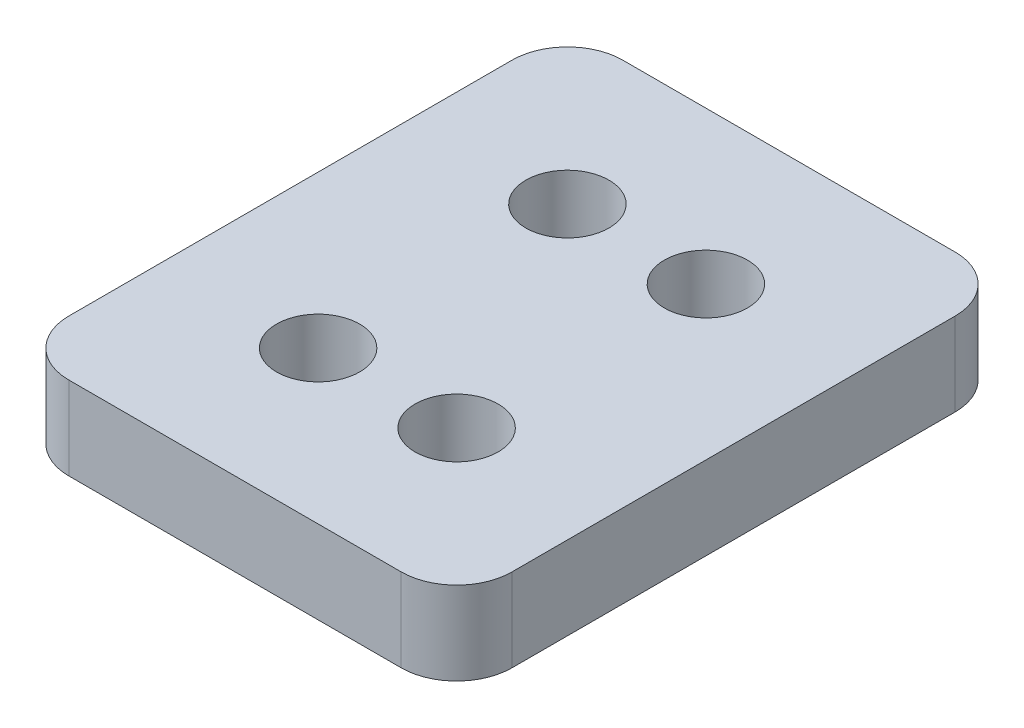
SolidWorks part; units mm, degrees
ref_plane "Plano frontal" through (0, 0, 0) normal (0, 0, 1) x (1, 0, 0)
ref_plane "Plano superior" through (0, 0, 0) normal (0, 1, 0) x (1, 0, 0)
ref_plane "Plano direito" through (0, 0, 0) normal (1, 0, 0) x (0, 0, -1)
sketch "Sketch1" plane through (0, 0, 0) normal (0, 1, 0) x (1, 0, 0)
  line L1 (-8, -10) -> (8, -10)
  line L2 (-8, -10) -> (-8, 10)
  line L3 (-8, 10) -> (8, 10)
  line L4 (8, -10) -> (8, 10)
  line L5 (-8, -10) -> (8, 10) construction
  line L6 (-8, 10) -> (8, -10) construction
  point P0 (0, 0)
  dimension "D1" = 16
  dimension "D2" = 20
extrude "Boss-Extrude1" add sketch "Sketch1" along normal mid plane 3
sketch "Sketch2" plane through (0, 1.5, 0) normal (0, 1, 0) x (1, 0, 0)
  circle A0 centre (2.5, -4.5) radius 1.5
  circle A1 centre (-2.5, -4.5) radius 1.5
  circle A2 centre (2.5, 4.5) radius 1.5
  circle A3 centre (-2.5, 4.5) radius 1.5
  dimension "D1" = 3
  dimension "D2" = 3
  dimension "D3" = 3
  dimension "D4" = 3
  dimension "D5" = 4.5
  dimension "D6" = 4.5
  dimension "D7" = 2.5
  dimension "D8" = 2.5
extrude "Cut-Extrude1" cut sketch "Sketch2" against normal blind 3 contours A1 | A3 | A2 | A0
fillet "Fillet1" radius 2 4 edges at (-8, 0, -10) (-8, 0, 10) (8, 0, 10) (8, 0, -10)
equation "\"D2@Sketch2\"=\"D1@Sketch2\""
equation "\"D3@Sketch2\"=\"D1@Sketch2\""
equation "\"D4@Sketch2\"=\"D1@Sketch2\""
equation "\"D6@Sketch2\"=\"D5@Sketch2\""
